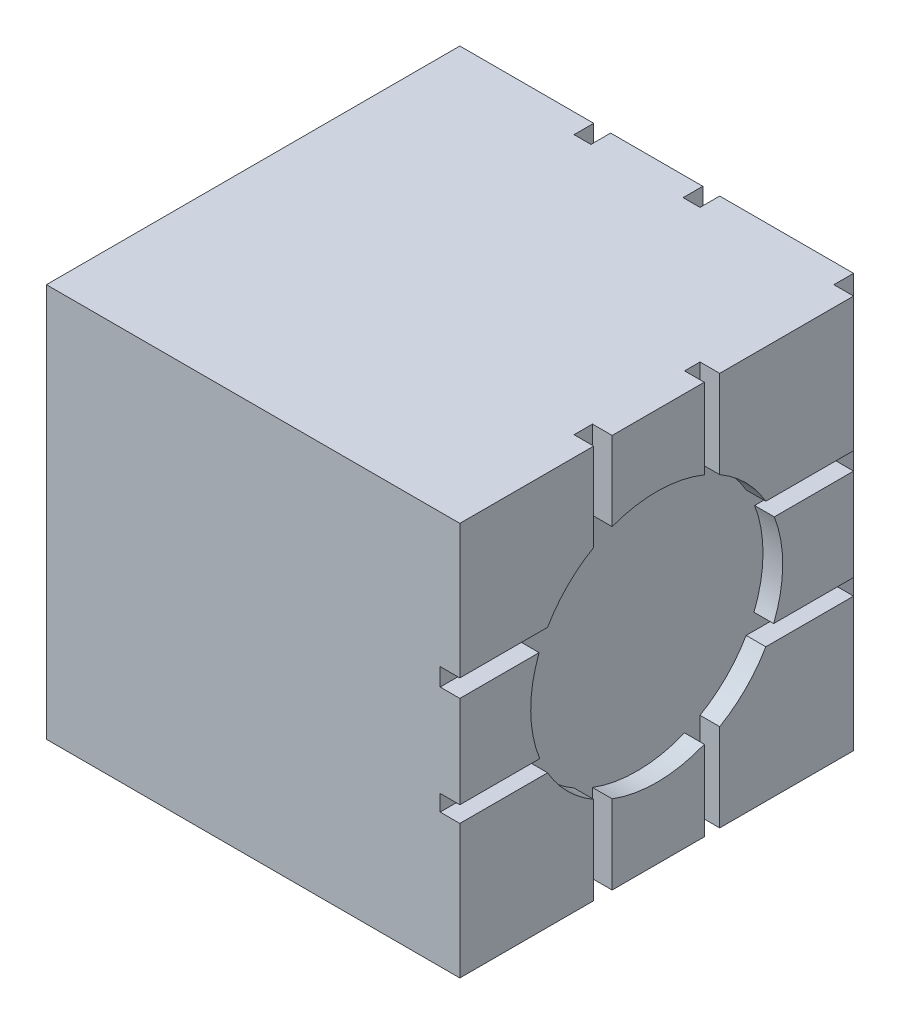
SolidWorks part; units mm, degrees
ref_plane "Front Plane" through (0, 0, 0) normal (0, 0, 1) x (1, 0, 0)
ref_plane "Top Plane" through (0, 0, 0) normal (0, 1, 0) x (1, 0, 0)
ref_plane "Right Plane" through (0, 0, 0) normal (1, 0, 0) x (0, 0, -1)
sketch "Sketch1" plane through (0, 0, 0) normal (0, 0, 1) x (1, 0, 0)
  line L1 (-63.5, -63.5) -> (63.5, -63.5)
  line L2 (-63.5, -63.5) -> (-63.5, 63.5)
  line L3 (-63.5, 63.5) -> (63.5, 63.5)
  line L4 (63.5, -63.5) -> (63.5, 63.5)
  line L5 (-63.5, -63.5) -> (63.5, 63.5) construction
  line L6 (-63.5, 63.5) -> (63.5, -63.5) construction
  point P0 (0, 0)
  dimension "D1" = 127
extrude "Boss-Extrude1" add sketch "Sketch1" along normal blind 127
sketch "Sketch4" plane through (0, 0, 0) normal (0, 0, -1) x (-1, 0, 0)
  circle A0 centre (0, 0) radius 31.115
other "Pen Sketch2" parameters "D1"=62.007
sketch "Sketch13" plane through (0, 0, 0) normal (0, 0, -1) x (-1, 0, 0)
  line L0 (-63.5, -63.5) -> (-63.5, 63.5) construction
  line L1 (-63.5, 63.5) -> (-20.32, 63.5)
  line L2 (-63.5, 63.5) -> (-63.5, 20.32)
  line L3 (-63.5, 20.32) -> (-20.32, 20.32)
  line L4 (-20.32, 63.5) -> (-20.32, 20.32)
  line L5 (-63.5, -63.5) -> (-20.32, -63.5)
  line L6 (63.5, 63.5) -> (20.32, 63.5)
  line L7 (63.5, 63.5) -> (63.5, 20.32)
  line L8 (63.5, 20.32) -> (20.32, 20.32)
  line L9 (20.32, 63.5) -> (20.32, 20.32)
  line L10 (-63.5, -63.5) -> (-63.5, -20.32)
  line L11 (-63.5, -20.32) -> (-20.32, -20.32)
  line L16 (-20.32, -63.5) -> (-20.32, -20.32)
  line L17 (63.5, -63.5) -> (20.32, -63.5)
  line L18 (63.5, -63.5) -> (63.5, -20.32)
  line L19 (63.5, -20.32) -> (20.32, -20.32)
  line L20 (20.32, -63.5) -> (20.32, -20.32)
  line L21 (-63.5, 14.859) -> (-33.782, 14.859)
  line L22 (-63.5, 14.859) -> (-63.5, -14.859)
  line L23 (-63.5, -14.859) -> (-33.782, -14.859)
  line L24 (-33.782, 14.859) -> (-33.782, -14.859)
  line L25 (63.5, -63.5) -> (-63.5, -63.5) construction
  line L26 (-14.859, -63.5) -> (14.859, -63.5)
  line L27 (-14.859, -63.5) -> (-14.859, -33.782)
  line L28 (-14.859, -33.782) -> (14.859, -33.782)
  line L29 (14.859, -63.5) -> (14.859, -33.782)
  line L30 (63.5, 63.5) -> (63.5, -63.5) construction
  line L31 (63.5, 14.859) -> (33.782, 14.859)
  line L32 (63.5, 14.859) -> (63.5, -14.859)
  line L33 (63.5, -14.859) -> (33.782, -14.859)
  line L34 (33.782, 14.859) -> (33.782, -14.859)
  line L40 (-63.5, 63.5) -> (63.5, 63.5) construction
  line L41 (-14.859, 63.5) -> (14.859, 63.5)
  line L42 (-14.859, 63.5) -> (-14.859, 33.782)
  line L43 (-14.859, 33.782) -> (14.859, 33.782)
  line L44 (14.859, 63.5) -> (14.859, 33.782)
  point P44 (-14.859, 48.641)
  dimension "D1" = 43.18
  dimension "D3" = 5.461
  dimension "D6" = 5.461
sketch "Sketch16" plane through (0, 0, 0) normal (0, 0, -1) x (-1, 0, 0)
sketch "Sketch27" plane through (63.5, 0, 0) normal (1, 0, 0) x (0, 0, -1)
  line L0 (-127, 63.5) -> (-83.82, 63.5)
  line L1 (-127, 63.5) -> (-127, 20.32)
  line L2 (-127, 20.32) -> (-83.82, 20.32)
  line L3 (-83.82, 63.5) -> (-83.82, 20.32)
  line L4 (-127, -63.5) -> (-83.82, -63.5)
  line L5 (0, 63.5) -> (-43.18, 63.5)
  line L6 (0, 63.5) -> (0, 20.32)
  line L7 (0, 20.32) -> (-43.18, 20.32)
  line L8 (-43.18, 63.5) -> (-43.18, 20.32)
  line L9 (-127, -63.5) -> (-127, -20.32)
  line L10 (-127, -20.32) -> (-83.82, -20.32)
  line L11 (-83.82, -63.5) -> (-83.82, -20.32)
  line L12 (0, -63.5) -> (-43.18, -63.5)
  line L13 (0, -63.5) -> (0, -20.32)
  line L14 (0, -20.32) -> (-43.18, -20.32)
  line L15 (-43.18, -63.5) -> (-43.18, -20.32)
  line L16 (-127, 14.6042) -> (-97.282, 14.6042)
  line L17 (-127, 14.6042) -> (-127, -15.1138)
  line L18 (-127, -15.1138) -> (-97.282, -15.1138)
  line L19 (-97.282, 14.6042) -> (-97.282, -15.1138)
  line L20 (-77.8726, -63.5) -> (-48.1546, -63.5)
  line L21 (-77.8726, -63.5) -> (-77.8726, -33.782)
  line L22 (-77.8726, -33.782) -> (-48.1546, -33.782)
  line L23 (-48.1546, -63.5) -> (-48.1546, -33.782)
  line L24 (0, 14.6042) -> (-29.718, 14.6042)
  line L25 (0, 14.6042) -> (0, -15.1138)
  line L26 (0, -15.1138) -> (-29.718, -15.1138)
  line L27 (-29.718, 14.6042) -> (-29.718, -15.1138)
  line L28 (-77.8726, 63.5) -> (-48.1546, 63.5)
  line L29 (-77.8726, 63.5) -> (-77.8726, 33.782)
  line L30 (-77.8726, 33.782) -> (-48.1546, 33.782)
  line L31 (-48.1546, 63.5) -> (-48.1546, 33.782)
  line L32 (-127, 63.5) -> (0, 63.5) construction
  line L33 (-127, -63.5) -> (-127, 63.5) construction
  line L34 (0, -63.5) -> (0, 63.5) construction
  line L35 (-127, -63.5) -> (0, -63.5) construction
  point P42 (-179.25, -8.2353)
sketch "Sketch28" plane through (63.5, 0, 0) normal (1, 0, 0) x (0, 0, -1)
  circle A1 centre (-63.5, 0) radius 40.64
extrude "Boss-Extrude7" add sketch "Sketch13" along normal blind 6.35
sketch "Sketch29" plane through (0, 0, 0) normal (0, 0, -1) x (-1, 0, 0)
  circle A0 centre (0, 0) radius 40.64
extrude "Cut-Extrude10" cut sketch "Sketch29" along normal blind 6.35
extrude "Boss-Extrude8" add sketch "Sketch27" along normal blind 6.35
sketch "Sketch30" plane through (63.5, 0, 0) normal (1, 0, 0) x (0, 0, -1)
  circle A0 centre (-63.5, 0) radius 31.115
  point P6 (0, 0)
  dimension "D1" = 62.23
extrude "Cut-Extrude11" cut sketch "Sketch28" along normal blind 6.35
sketch "Sketch32" plane through (0, 63.5, 0) normal (0, 1, 0) x (0, 0, -1)
  line L0 (-104.7634, 84.79) -> (-61.5834, 84.79)
  line L1 (-104.7634, 84.79) -> (-104.7634, 41.61)
  line L2 (-104.7634, 41.61) -> (-61.5834, 41.61)
  line L3 (-61.5834, 84.79) -> (-61.5834, 41.61)
  line L4 (-104.7634, -42.21) -> (-61.5834, -42.21)
  line L5 (22.2366, 84.79) -> (-20.9434, 84.79)
  line L6 (22.2366, 84.79) -> (22.2366, 41.61)
  line L7 (22.2366, 41.61) -> (-20.9434, 41.61)
  line L8 (-20.9434, 84.79) -> (-20.9434, 41.61)
  line L9 (-104.7634, -42.21) -> (-104.7634, 0.97)
  line L10 (-104.7634, 0.97) -> (-61.5834, 0.97)
  line L11 (-61.5834, -42.21) -> (-61.5834, 0.97)
  line L12 (22.2366, -42.21) -> (-20.9434, -42.21)
  line L13 (22.2366, -42.21) -> (22.2366, 0.97)
  line L14 (22.2366, 0.97) -> (-20.9434, 0.97)
  line L15 (-20.9434, -42.21) -> (-20.9434, 0.97)
  line L16 (-104.7634, 35.8943) -> (-75.0454, 35.8943)
  line L17 (-104.7634, 35.8943) -> (-104.7634, 6.1763)
  line L18 (-104.7634, 6.1763) -> (-75.0454, 6.1763)
  line L19 (-75.0454, 35.8943) -> (-75.0454, 6.1763)
  line L20 (-55.636, -42.21) -> (-25.918, -42.21)
  line L21 (-55.636, -42.21) -> (-55.636, -12.492)
  line L22 (-55.636, -12.492) -> (-25.918, -12.492)
  line L23 (-25.918, -42.21) -> (-25.918, -12.492)
  line L24 (22.2366, 35.8943) -> (-7.4814, 35.8943)
  line L25 (22.2366, 35.8943) -> (22.2366, 6.1763)
  line L26 (22.2366, 6.1763) -> (-7.4814, 6.1763)
  line L27 (-7.4814, 35.8943) -> (-7.4814, 6.1763)
  line L28 (-55.636, 84.79) -> (-25.918, 84.79)
  line L29 (-55.636, 84.79) -> (-55.636, 55.072)
  line L30 (-55.636, 55.072) -> (-25.918, 55.072)
  line L31 (-25.918, 84.79) -> (-25.918, 55.072)
  point P32 (-217.5785, 54.6534)
  point P42 (-157.0134, 13.0547)
